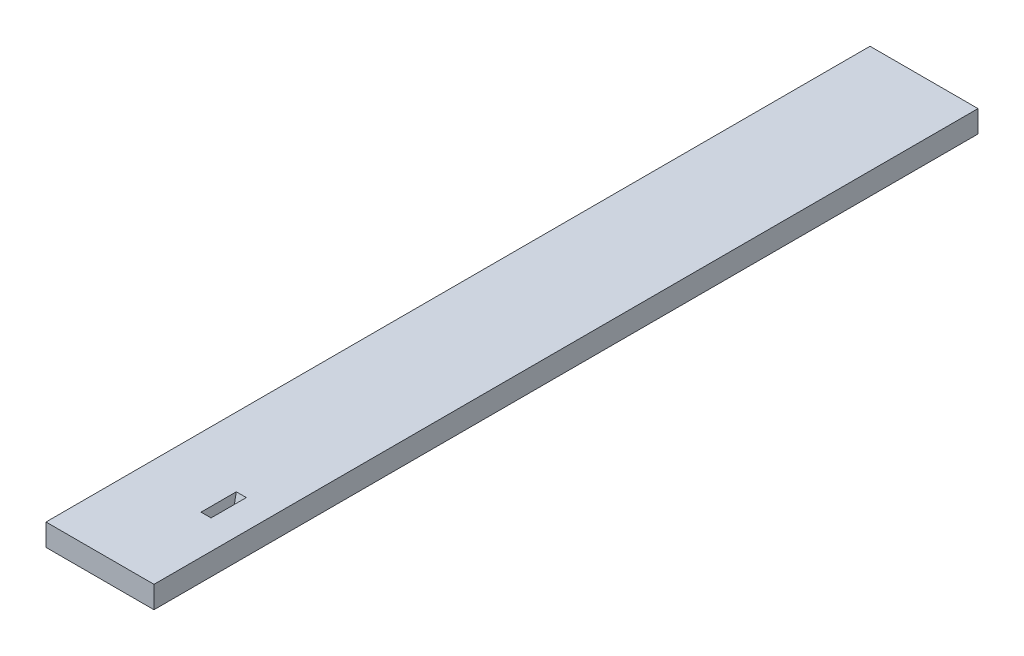
SolidWorks part; units mm, degrees
ref_plane "前基準面" through (0, 0, 0) normal (0, 0, 1) x (1, 0, 0)
ref_plane "上基準面" through (0, 0, 0) normal (0, 1, 0) x (1, 0, 0)
ref_plane "右基準面" through (0, 0, 0) normal (1, 0, 0) x (0, 0, -1)
sketch "草圖1" plane through (0, 0, 0) normal (0, 0, 1) x (1, 0, 0)
  line L0 (-291.2917, -566) -> (312.6351, -566) construction
  line L1 (-98, 40) -> (98, 40)
  line L2 (-98, 40) -> (-98, 0)
  line L3 (-98, 0) -> (98, 0)
  line L4 (98, 40) -> (98, 0)
  line L5 (67.7, 40) -> (158.6, -566) construction
  line L6 (27.2525, 40) -> (141.2697, -720.1148) construction
  line L7 (0, 184.4246) -> (0, -587.9737) construction
  line L8 (-27.2525, 40) -> (-141.2697, -720.1148) construction
  line L9 (-67.7, 40) -> (-158.6, -566) construction
  point P17 (33.2525, 0)
  point P18 (73.7, 0)
  dimension "D1" = 196
  dimension "D2" = 40
  dimension "D3" = 606
  dimension "D4" = 30.3
  dimension "D5" = 60.6
  dimension "D6" = 40
sketch "草圖2" plane through (0, 0, 0) normal (1, 0, 0) x (0, 0, -1)
  line L0 (583.3, 68.2609) -> (871.2, -702.9739) construction
  line L1 (-750, 40) -> (750, 40)
  line L2 (-750, 40) -> (-750, 0)
  line L3 (-750, 0) -> (750, 0)
  line L4 (750, 40) -> (750, 0)
  line L5 (510.0405, 92.9471) -> (800.2264, -684.4113) construction
  line L6 (0, 184.4246) -> (0, -861.7981) construction
  line L7 (0, 184.4246) -> (0, -587.9737) construction
  line L8 (-510.0405, 92.9471) -> (-800.2264, -684.4113) construction
  line L9 (-583.3, 68.2609) -> (-871.2, -702.9739) construction
  point P19 (-608.7816, 0)
  point P20 (-544.7374, 0)
  point P21 (-593.8497, 40)
  point P22 (-529.8055, 40)
  point P23 (529.8055, 40)
  point P24 (544.7374, 0)
  point P25 (593.8497, 40)
  point P26 (608.7816, 0)
  dimension "D1" = 1500
  dimension "D2" = 166.7
  dimension "D3" = 121.2
  dimension "D4" = 60
sketch "草圖3" plane through (0, 0, 0) normal (0, 1, 0) x (1, 0, 0)
  line L1 (-98, 745.7095) -> (98, 745.7095) construction
  line L2 (-98, 745.7095) -> (-98, -750) construction
  line L3 (-98, -750) -> (98, -750) construction
  line L4 (98, 745.7095) -> (98, -750) construction
ref_plane "平面1" through (0, 40, 0) normal (0, 1, 0) x (-1, 0, 0)
sketch "草圖4" plane through (0, 40, 0) normal (0, 1, 0) x (-1, 0, 0)
  line L0 (98, 593.8497) -> (-98, 593.8497) construction
  line L1 (-98, 750) -> (98, 750) construction
  line L2 (-98, 750) -> (-98, -745.7095) construction
  line L3 (-98, -745.7095) -> (98, -745.7095) construction
  line L4 (98, 750) -> (98, -745.7095) construction
  line L5 (98, 529.8055) -> (-98, 529.8055) construction
  line L6 (-67.7, 0) -> (-67.7, 750) construction
  line L7 (-27.2525, 0) -> (-27.2525, 750) construction
  line L8 (-98, 750) -> (98, 750)
  line L9 (-98, 750) -> (-98, -745.7095)
  line L10 (-98, -745.7095) -> (98, -745.7095)
  line L11 (98, 750) -> (98, -745.7095)
  line L13 (-45.4325, 593.8497) -> (-27.2525, 593.8497) construction
  line L14 (-45.4325, 593.8497) -> (-45.4325, 529.8055) construction
  line L15 (-45.4325, 529.8055) -> (-27.2525, 529.8055) construction
  line L16 (-27.2525, 593.8497) -> (-27.2525, 529.8055) construction
  dimension "D1" = 18.18
sketch "草圖5" plane through (0, 0, 0) normal (0, 0, 1) x (1, 0, 0)
  line L0 (-98, 0) -> (98, 0) construction
  line L1 (-98, 40) -> (98, 40) construction
  line L3 (-27.2525, 40) -> (-141.2697, -720.1148) construction
  line L4 (-67.7, 40) -> (-158.6, -566) construction
  line L5 (27.2525, 40) -> (141.2697, -720.1148) construction
  line L6 (67.7, 40) -> (158.6, -566) construction
  point P0 (-67.7, 40)
  point P1 (-73.7, 0)
  point P3 (-33.2525, 0)
  point P6 (-27.2525, 40)
  point P7 (67.7, 40)
  point P10 (73.7, 0)
  point P12 (33.2525, 0)
  point P13 (27.2525, 40)
ref_plane "平面2" through (0, 0, 750) normal (0, 0, 1) x (1, 0, 0)
sketch "草圖7" plane through (0, 0, 750) normal (0, 0, 1) x (1, 0, 0)
  line L0 (98, 40) -> (-98, 40) construction
  line L1 (-98.2112, 40) -> (98.53, 40)
  line L2 (-98.2112, 40) -> (-98.2112, 0)
  line L3 (-98.2112, 0) -> (98.53, 0)
  line L4 (98.53, 40) -> (98.53, 0)
  line L5 (-98, 0) -> (98, 0) construction
  line L6 (27.2525, 40) -> (33.2525, 0) construction
  line L7 (67.7, 40) -> (73.7, 0) construction
sketch "草圖8" plane through (0, 0, 0) normal (0, 1, 0) x (1, 0, 0)
  line L0 (33.2525, -750) -> (33.2525, 846.4747) construction
  line L1 (73.7, -750) -> (73.7, -448.7343) construction
  line L2 (-98, -750) -> (98, -750) construction
  line L3 (67.7, -750) -> (73.7, -750) construction
ref_plane "平面3" through (98.53, 0, 0) normal (1, 0, 0) x (0, 0, -1)
sketch "草圖9" plane through (98.53, 0, 0) normal (1, 0, 0) x (0, 0, -1)
  line L0 (-583.3, 68.2609) -> (-644.6713, -96.1422) construction
  line L1 (-583.3, 68.2609) -> (-871.2, -702.9739) construction
  line L2 (-510.0405, 92.9471) -> (-580.627, -96.1422) construction
  line L3 (-510.0405, 92.9471) -> (-800.2264, -684.4113) construction
sketch "草圖10" plane through (0, 0, 0) normal (0, 1, 0) x (1, 0, 0)
  line L0 (98.53, -608.7816) -> (-98.0201, -608.7816) construction
  line L3 (98.53, -544.7374) -> (-107.7463, -544.7374) construction
  line L4 (33.2525, -750) -> (33.2525, 846.4747) construction
  line L7 (51.4325, -608.7816) -> (33.2525, -608.7816)
  line L8 (51.4325, -608.7816) -> (51.4325, -544.7374)
  line L9 (51.4325, -544.7374) -> (33.2525, -544.7374)
  line L10 (33.2525, -608.7816) -> (33.2525, -544.7374)
  dimension "D1" = 18.18
extrude "填料-伸長2" add sketch "草圖4" against normal blind 40
ref_plane "平面4" through (50.3007, 7.5451, 0) normal (0.9889, 0.1483, 0) x (0, 0, -1)
sketch "草圖11" plane through (50.3007, 7.5451, 0) normal (0.9889, 0.1483, 0) x (0, 0, -1)
  line L0 (-593.8497, 32.818) -> (-608.7816, -7.6295)
extrude "除料-伸長1" cut sketch "草圖10" along direction (0.1392, -0.9277, 0.3463) on the side of the normal up to surface (43.1157 mm away)
